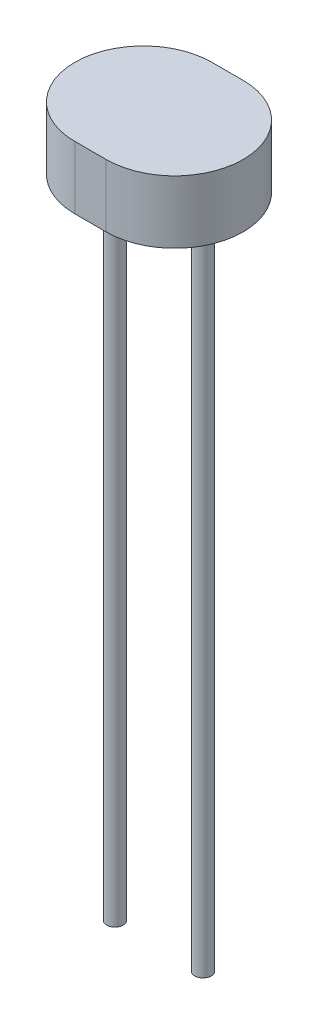
SolidWorks part; units mm, degrees
ref_plane "Alzado" through (0, 0, 0) normal (0, 0, 1) x (1, 0, 0)
ref_plane "Planta" through (0, 0, 0) normal (0, 1, 0) x (1, 0, 0)
ref_plane "Vista lateral" through (0, 0, 0) normal (1, 0, 0) x (0, 0, -1)
sketch "Croquis1" plane through (0, 0, 0) normal (0, 1, 0) x (1, 0, 0)
  line L0 (-0.475, 0) -> (0.475, 0) construction
  line L1 (-0.475, 2.075) -> (0.475, 2.075)
  line L2 (-0.475, -2.075) -> (0.475, -2.075)
  arc A0 (-0.475, 2.075) -> (-0.475, -2.075) centre (-0.475, 0) ccw
  arc A1 (0.475, -2.075) -> (0.475, 2.075) centre (0.475, 0) ccw
  point P3 (0, 0)
  dimension "D1" = 4.15
  dimension "D2" = 0.95
extrude "Saliente-Extruir1" add sketch "Croquis1" along normal blind 1.9
sketch "Croquis3" plane through (0, 0, 0) normal (0, -1, 0) x (1, 0, 0)
  line L0 (0, -1.045) -> (0, 1.045) construction
  circle A0 centre (-1.3337, 0) radius 0.25
  circle A1 centre (1.3337, 0) radius 0.25
  dimension "D1" = 0.5
extrude "Saliente-Extruir2" add sketch "Croquis3" along normal blind 20
sketch "Sketch1" plane through (0, 1.9, 0) normal (0, 1, 0) x (1, 0, 0)
  line L0 (-2.55, 0) -> (2.55, 0) construction
  arc A0 (-0.475, 2.075) -> (-0.475, -2.075) centre (-0.475, 0) ccw construction
  arc A1 (0.475, -2.075) -> (0.475, 2.075) centre (0.475, 0) ccw construction
  point P0 (-2.55, 0)
  point P1 (2.55, 0)
  point P5 (0, 0)
